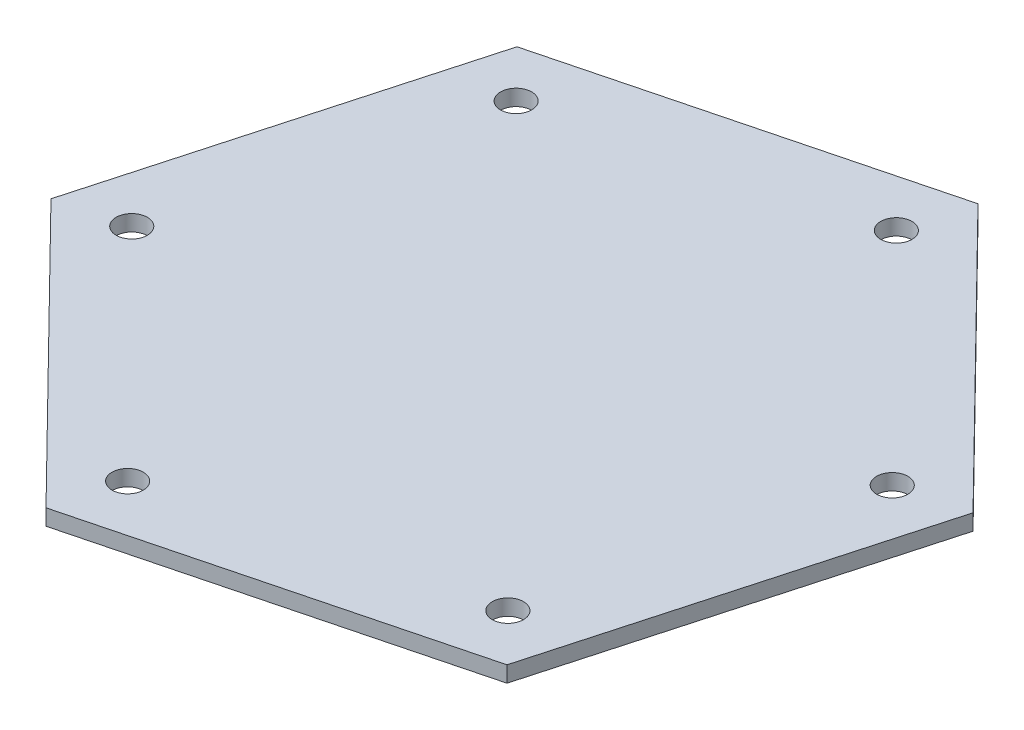
SolidWorks part; units mm, degrees
ref_plane "Front Plane" through (0, 0, 0) normal (0, 0, 1) x (1, 0, 0)
ref_plane "Top Plane" through (0, 0, 0) normal (0, 1, 0) x (1, 0, 0)
ref_plane "Right Plane" through (0, 0, 0) normal (1, 0, 0) x (0, 0, -1)
sketch "Sketch1" plane through (0, 0, 0) normal (0, 1, 0) x (1, 0, 0)
  line L1 (21.5725, -21.9776) -> (29.8194, 7.6935)
  line L2 (29.8194, 7.6935) -> (8.2469, 29.6711)
  line L3 (8.2469, 29.6711) -> (-21.5725, 21.9776)
  line L4 (-21.5725, 21.9776) -> (-29.8194, -7.6935)
  line L5 (-29.8194, -7.6935) -> (-8.2469, -29.6711)
  line L6 (-8.2469, -29.6711) -> (21.5725, -21.9776)
  circle A0 centre (0, 0) radius 26.67 construction
  dimension "D1" = 53.34
extrude "Boss-Extrude1" add sketch "Sketch1" along normal blind 1.3
sketch "Sketch2" plane through (0, 0, 0) normal (0, 1, 0) x (1, 0, 0)
  line L0 (0, 0) -> (8.2469, 29.6711) construction
  circle A0 centre (0, 0) radius 25.4 construction
  circle A1 centre (6.8019, 24.4723) radius 1.27
  circle A2 centre (24.5946, 6.3455) radius 1.27
  circle A3 centre (17.7927, -18.1268) radius 1.27
  circle A4 centre (-6.8019, -24.4723) radius 1.27
  circle A5 centre (-24.5946, -6.3455) radius 1.27
  circle A6 centre (-17.7927, 18.1268) radius 1.27
  point P19 (0, 0)
  dimension "D1" = 50.8
  dimension "D2" = 2.54
  dimension "D3" = 6
extrude "Cut-Extrude2" cut sketch "Sketch2" along normal through all
